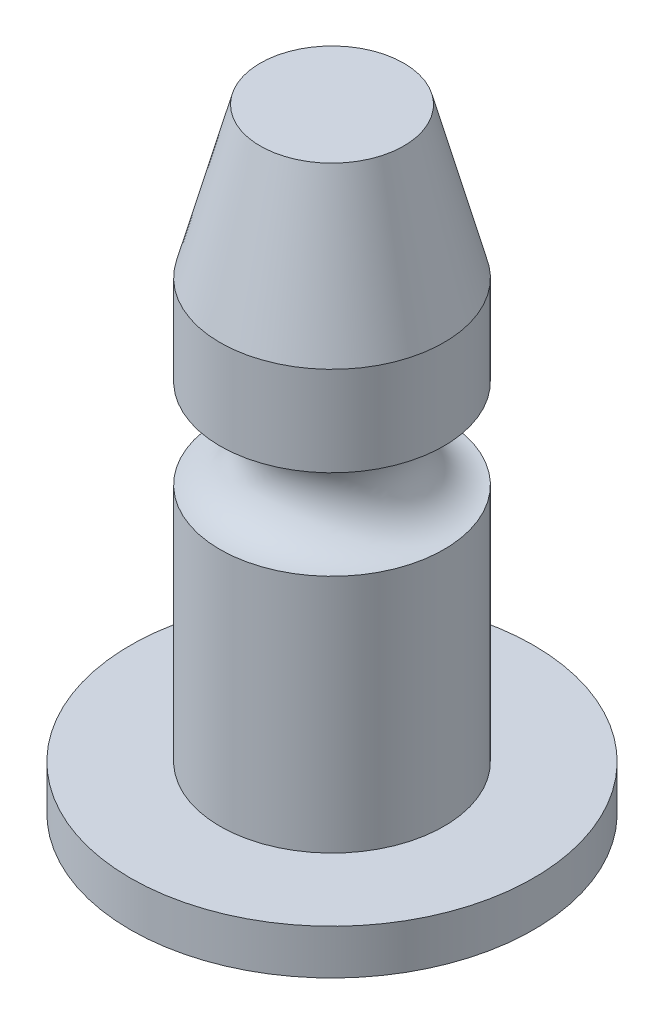
SolidWorks part; units mm, degrees
ref_plane "Front Plane" through (0, 0, 0) normal (0, 0, 1) x (1, 0, 0)
ref_plane "Top Plane" through (0, 0, 0) normal (0, 1, 0) x (1, 0, 0)
ref_plane "Right Plane" through (0, 0, 0) normal (1, 0, 0) x (0, 0, -1)
sketch "Sketch1" plane through (0, 0, 0) normal (0, 0, 1) x (1, 0, 0)
  line L0 (0, 6.35) -> (-1.6024, 6.35)
  line L1 (-1.6024, 6.35) -> (-2.5, 3)
  line L2 (-2.5, 3) -> (-2.5, 1)
  line L3 (-4.5, -6.35) -> (-4.5, -7.35)
  line L4 (-2.5, -1) -> (-2.5, -6.35)
  line L5 (-2.5, -6.35) -> (-4.5, -6.35)
  line L6 (-4.5, -7.35) -> (0, -7.35)
  line L7 (0, 0) -> (0, 50000) construction
  line L8 (0, 6.35) -> (0, -7.35)
  arc A0 (-2.5, 1) -> (-2.5, -1) centre (-2.5, 0) cw
  dimension "D3" = 1
  dimension "D1" = 6.35
  dimension "D2" = 6.35
  dimension "D4" = 2.5
  dimension "D5" = 15
  dimension "D6" = 1
  dimension "D7" = 2
  dimension "D8" = 2
revolve "Revolve1" add sketch "Sketch1" angle 360 about L7
equation "\"inner_tube_thickness\"= .25in"
equation "\"outer_tube_thickness\"= .25in"
equation "\"D1@Sketch1\"=\"inner_tube_thickness\""
equation "\"D2@Sketch1\"=\"outer_tube_thickness\""
